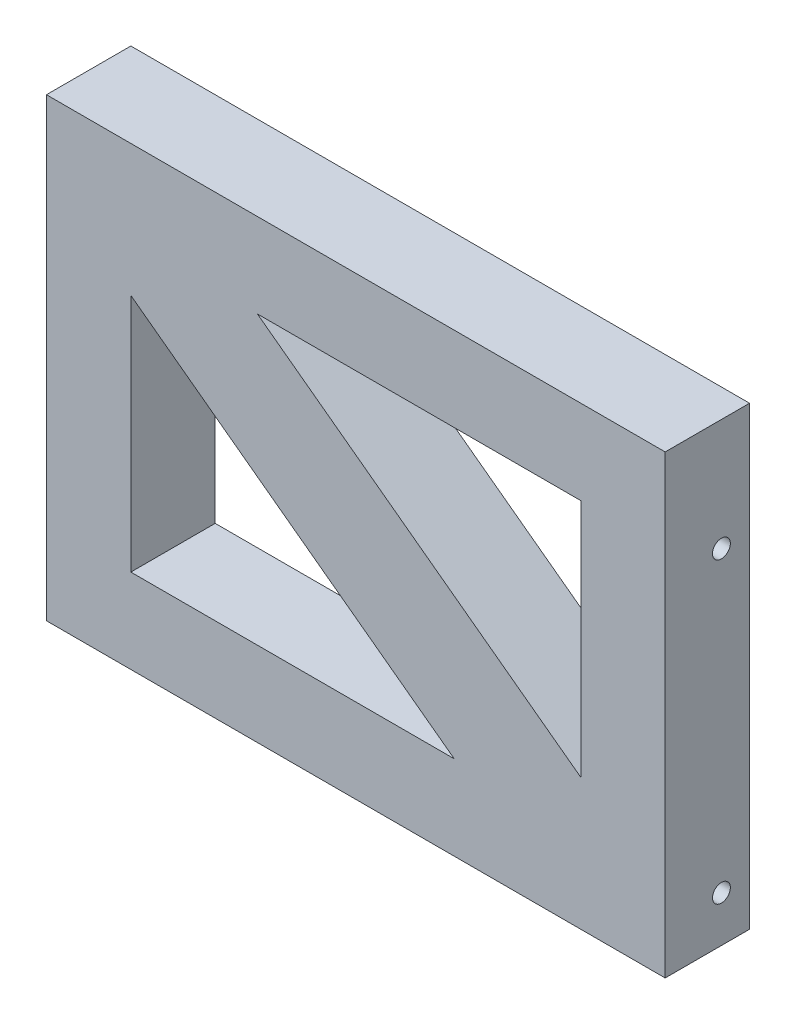
SolidWorks part; units mm, degrees
material "ABS"
ref_plane "Front Plane" through (0, 0, 0) normal (0, 0, 1) x (1, 0, 0)
ref_plane "Top Plane" through (0, 0, 0) normal (0, 1, 0) x (1, 0, 0)
ref_plane "Right Plane" through (0, 0, 0) normal (1, 0, 0) x (0, 0, -1)
sketch "Sketch1" plane through (0, 0, 0) normal (0, 0, 1) x (1, 0, 0)
  line L0 (19.05, 19.05) -> (19.05, 73.152)
  line L1 (0, 0) -> (139.7, 0)
  line L2 (0, 0) -> (0, 102.87)
  line L3 (0, 102.87) -> (139.7, 102.87)
  line L4 (139.7, 0) -> (139.7, 102.87)
  line L5 (19.05, 19.05) -> (92.075, 19.05)
  line L6 (19.05, 73.152) -> (92.075, 19.05)
  line L7 (120.65, 83.82) -> (120.65, 29.718)
  line L8 (120.65, 83.82) -> (47.625, 83.82)
  line L9 (47.625, 83.82) -> (120.65, 29.718)
  dimension "D1" = 19.05
  dimension "D2" = 19.05
  dimension "D3" = 73.025
  dimension "D4" = 54.102
  dimension "D5" = 19.05
  dimension "D6" = 139.7
  dimension "D7" = 73.025
  dimension "D8" = 54.102
  dimension "D9" = 19.05
  dimension "D10" = 102.87
extrude "Boss-Extrude1" add sketch "Sketch1" along normal blind 19.05
hole_wizard "#10-32 Tapped Hole2" positions "3DSketch2" profile "Sketch3" tap size "#10-32" standard "Ansi Inch"
sketch3d "3DSketch2"
  line L0 (0, 102.87, 6.35) -> (0, 0, 6.35) construction
  line L1 (0, 102.87, 19.05) -> (0, 102.87, 0) construction
  line L2 (0, 0, 19.05) -> (0, 0, 0) construction
  line L3 (0, 102.87, 0) -> (0, 0, 0) construction
  line L4 (0, 77.6326, 0) -> (0, 77.6326, 19.05) construction
  line L5 (0, 102.87, 19.05) -> (0, 0, 19.05) construction
  line L6 (0, 10.3226, 0) -> (0, 10.3226, 19.05) construction
  line L10 (139.7, 102.87, 6.35) -> (139.7, 0, 6.35) construction
  line L11 (139.7, 102.87, 19.05) -> (139.7, 102.87, 0) construction
  line L12 (139.7, 0, 19.05) -> (139.7, 0, 0) construction
  line L13 (139.7, 0, 0) -> (139.7, 102.87, 0) construction
  line L14 (139.7, 77.6326, 19.05) -> (139.7, 77.6326, 0) construction
  line L15 (139.7, 0, 19.05) -> (139.7, 102.87, 19.05) construction
  line L16 (139.7, 10.3226, 19.05) -> (139.7, 10.3226, 0) construction
  point P0 (0, 77.6326, 6.35)
  point P2 (0, 10.3226, 6.35)
  point P4 (139.7, 10.3226, 6.35)
  point P6 (139.7, 77.6326, 6.35)
  dimension "D1" = 6.35
  dimension "D2" = 25.2374
  dimension "D3" = 92.5474
  dimension "D4" = 6.35
  dimension "D5" = 25.2374
  dimension "D6" = 92.5474
sketch "Sketch3" plane through (0, 77.6326, 6.35) normal (0, 1, 0) x (0, 0, 1)
  line L0 (0, 0) -> (0, 14.9293)
  line L1 (0, 14.9293) -> (2.0193, 13.716)
  line L2 (2.0193, 13.716) -> (2.0193, 0)
  line L5 (2.0193, 0) -> (0, 0)
  line L10 (0, 14.9293) -> (-2.0193, 13.716) construction
  line L11 (0, -6.35) -> (0, 107.95) construction
  dimension "Tap Drill Dia." = 4.0386
  dimension "Tap Drill Depth" = 13.716
  dimension "Drill Angle" = 118
cosmetic thread "Hole Thread5"
cosmetic thread "Hole Thread6"
cosmetic thread "Hole Thread7"
cosmetic thread "Hole Thread8"
